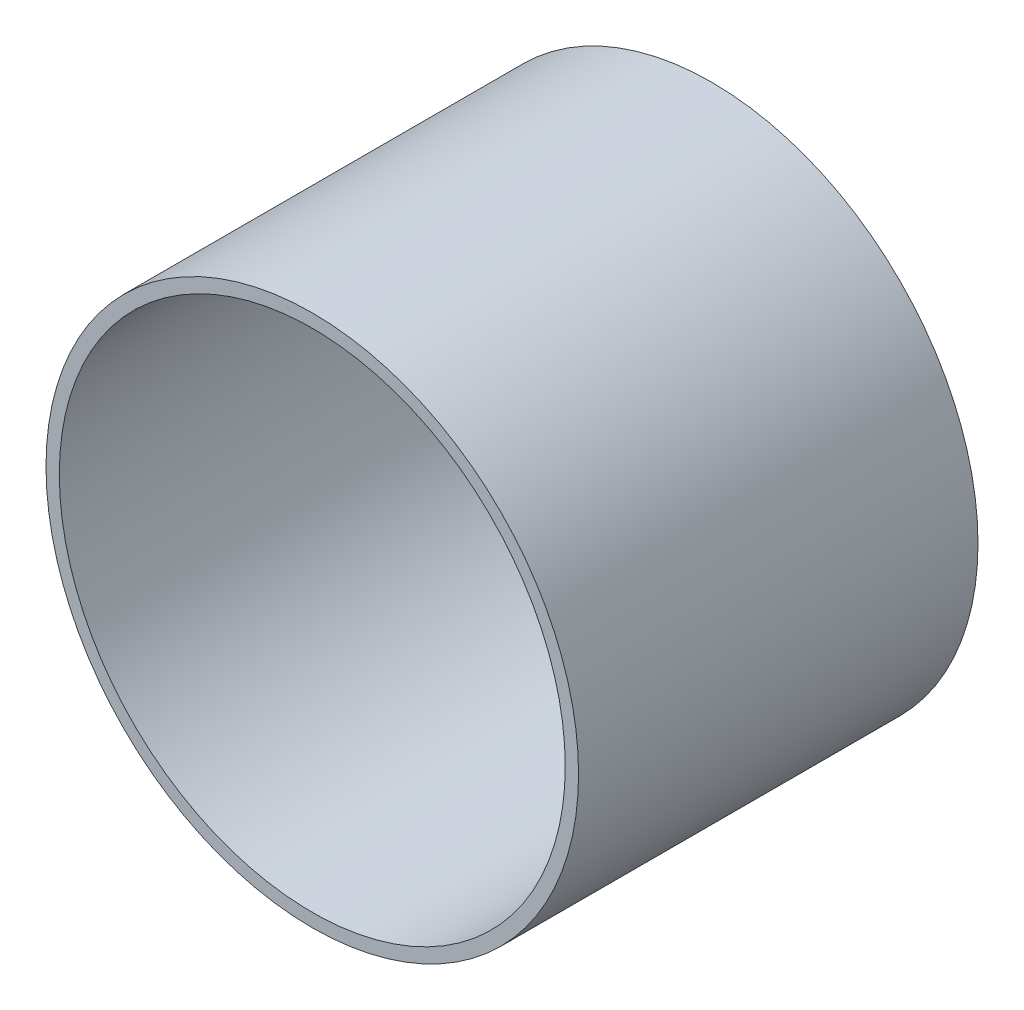
SolidWorks part; units mm, degrees
ref_plane "Front Plane" through (0, 0, 0) normal (0, 0, 1) x (1, 0, 0)
ref_plane "Top Plane" through (0, 0, 0) normal (0, 1, 0) x (1, 0, 0)
ref_plane "Right Plane" through (0, 0, 0) normal (1, 0, 0) x (0, 0, -1)
sketch "Sketch1" plane through (0, 0, 0) normal (0, 0, 1) x (1, 0, 0)
  circle A0 centre (0, 0) radius 100
  dimension "D1" = 200
extrude "Boss-Extrude1" add sketch "Sketch1" along normal blind 160
sketch "Sketch2" plane through (0, 0, 0) normal (0, 0, -1) x (-1, 0, 0)
  circle A0 centre (0, 0) radius 95
  dimension "D1" = 190
extrude "Cut-Extrude1" cut sketch "Sketch2" against normal blind 150
sketch "Sketch3" plane through (0, 0, 160) normal (0, 0, 1) x (1, 0, 0)
  circle A0 centre (0, 0) radius 10
  dimension "D1" = 20
extrude "Cut-Extrude2" cut sketch "Sketch3" against normal blind 150
ref_plane "Plane1" through (-100, 0, 0) normal (-1, 0, 0) x (0, 0, 1)
sketch "Sketch8" plane through (0, 0, 160) normal (0, 0, 1) x (1, 0, 0)
  circle A0 centre (0, 0) radius 100
extrude "Cut-Extrude4" cut sketch "Sketch8" against normal blind 10
